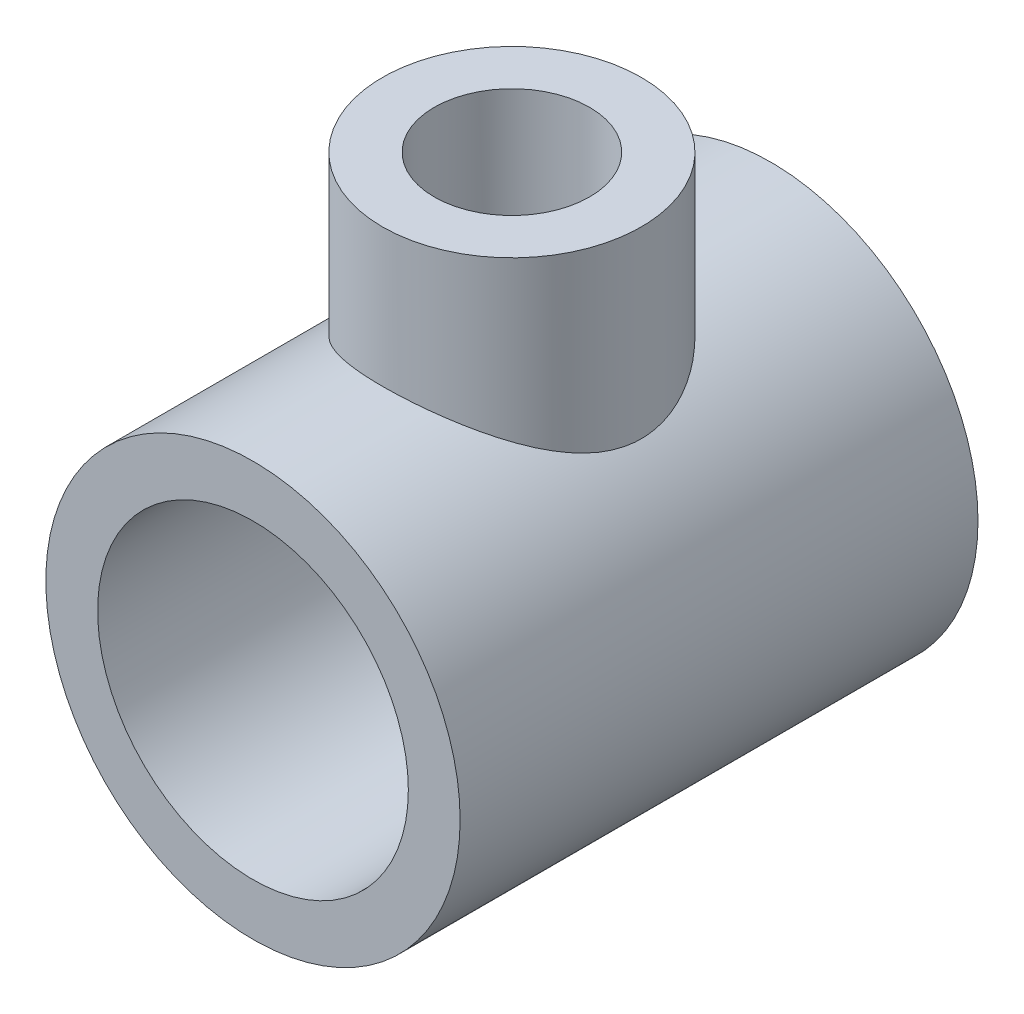
SolidWorks part; units mm, degrees
ref_plane "Alzado" through (0, 0, 0) normal (0, 0, 1) x (1, 0, 0)
ref_plane "Planta" through (0, 0, 0) normal (0, 1, 0) x (1, 0, 0)
ref_plane "Vista lateral" through (0, 0, 0) normal (1, 0, 0) x (0, 0, -1)
sketch "Croquis1" plane through (0, 0, 0) normal (0, 0, 1) x (1, 0, 0)
  circle A0 centre (0, 0) radius 18
  circle A1 centre (0, 0) radius 24
  dimension "D1" = 36
  dimension "D2" = 6
extrude "Saliente-Extruir1" add sketch "Croquis1" along normal mid plane 60
sketch "Croquis2" plane through (0, 0, 0) normal (0, 1, 0) x (1, 0, 0)
  circle A0 centre (0, 0) radius 9
  circle A1 centre (0, 0) radius 15
  dimension "D1" = 18
  dimension "D2" = 6
extrude "Saliente-Extruir2" add sketch "Croquis2" along normal blind 40
